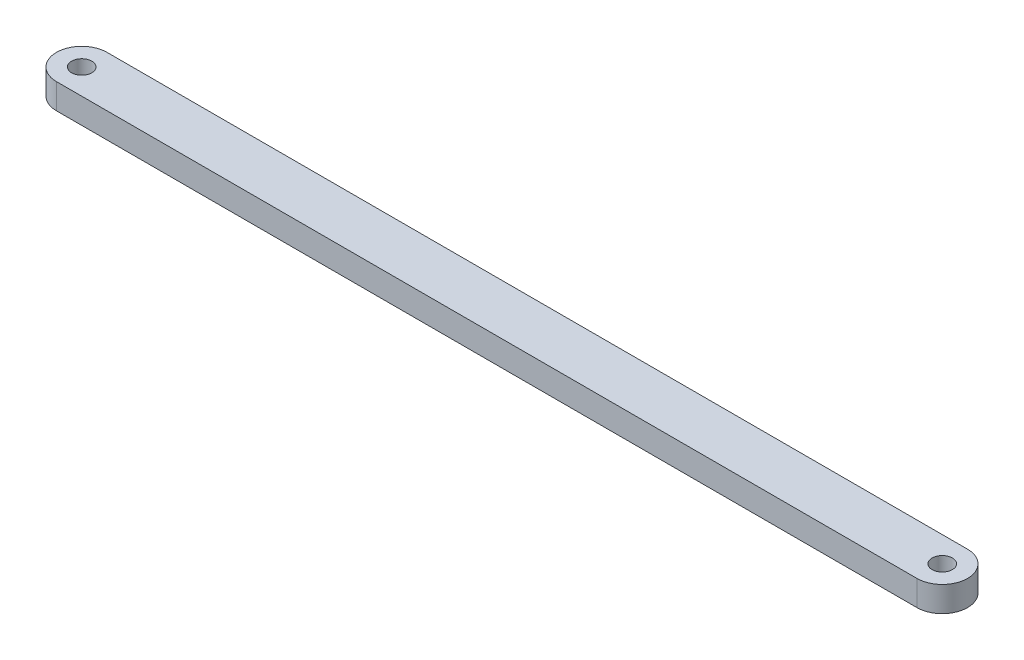
SolidWorks part; units mm, degrees
ref_plane "前视基准面" through (0, 0, 0) normal (0, 0, 1) x (1, 0, 0)
ref_plane "上视基准面" through (0, 0, 0) normal (0, 1, 0) x (1, 0, 0)
ref_plane "右视基准面" through (0, 0, 0) normal (1, 0, 0) x (0, 0, -1)
sketch "草图1" plane through (0, 0, 0) normal (0, 1, 0) x (1, 0, 0)
  line L0 (0, 0) -> (-170, 0)
  line L2 (-170, 10) -> (0, 10)
  arc A0 (-170, 10) -> (-170, 0) centre (-170, 5) ccw
  arc A1 (0, 0) -> (0, 10) centre (0, 5) ccw
  dimension "D1" = 170
  dimension "D2" = 10
extrude "凸台-拉伸1" add sketch "草图1" along normal blind 5
sketch "草图2" plane through (0, 5, 0) normal (0, 1, 0) x (1, 0, 0)
  line L0 (-170, 0) -> (-170, 10) construction
  line L1 (0, 0) -> (0, 10) construction
  circle A0 centre (-170, 5) radius 2
  circle A1 centre (0, 5) radius 2
extrude "切除-拉伸1" cut sketch "草图2" against normal blind 5
